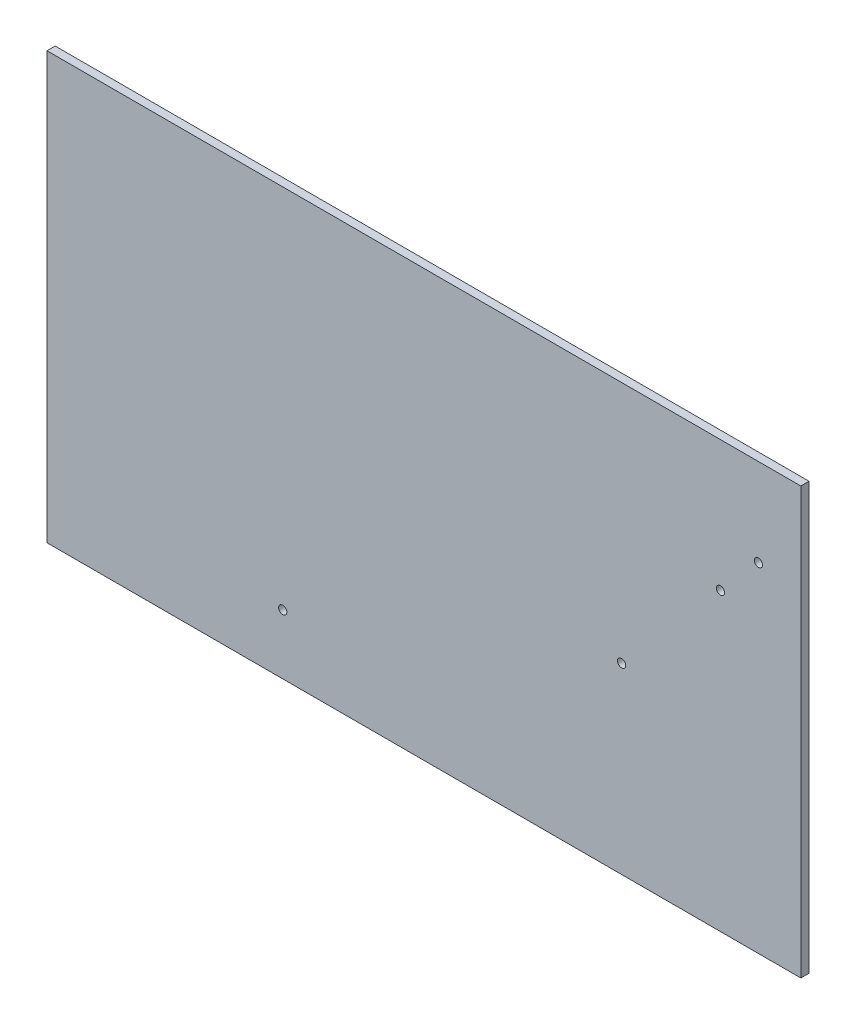
SolidWorks part; units mm, degrees
material "Thornel Mat VMA"
ref_plane "Front Plane" through (0, 0, 0) normal (0, 0, 1) x (1, 0, 0)
ref_plane "Top Plane" through (0, 0, 0) normal (0, 1, 0) x (1, 0, 0)
ref_plane "Right Plane" through (0, 0, 0) normal (1, 0, 0) x (0, 0, -1)
sketch "Sketch1" plane through (0, 0, 0) normal (0, 0, 1) x (1, 0, 0)
  line L0 (584.2, 0) -> (566.8254, 47.7364) construction
  line L3 (0, 330.2) -> (584.2, 330.2)
  line L5 (584.2, 330.2) -> (566.8254, 47.7364) construction
  line L6 (584.2, 0) -> (584.2, 330.2)
  line L7 (566.8254, 47.7364) -> (30.8772, 0.4906) construction
  line L8 (19.7249, 0) -> (0, 0) construction
  line L9 (0, 0) -> (0, 330.2)
  line L10 (0, 0) -> (584.2, 0)
  line L11 (182.7176, 46.2772) -> (445.2677, 141.8376) construction
  line L12 (551.2995, 262.3185) -> (521.9333, 228.9505) construction
  arc A0 (30.8772, 0.4906) -> (19.7249, 0) centre (19.7249, 127) cw construction
  circle A1 centre (182.7176, 46.2772) radius 3.175
  circle A2 centre (445.2677, 141.8376) radius 3.175
  circle A3 centre (521.9333, 228.9505) radius 3.175
  circle A4 centre (551.2995, 262.3185) radius 3.175
  spline S0 degree 2 poles (584.2, 330.2) (566.8254, 47.7364) (30.8772, 0.4906) knots 0 0 0 1 1 1 construction
  spline S1 degree 1 poles (558.8479, 331.7594) (28.6467, 25.7925) knots 0 0 1 1 construction
  spline S2 degree 2 poles (558.8479, 331.7594) (558.3508, 323.6772) (555.482, 300.2083) (548.0448, 270.8817) (537.017, 243.3493) (518.6822, 210.9611) (484.8837, 171.5386) (457.197, 150.374) (442.9828, 139.9187) (411.1198, 120.2243) (352.6628, 91.7959) (262.7906, 62.7429) (209.2344, 51.5081) (182.3957, 45.9179) (95.7948, 31.7202) (28.6467, 25.7925) knots 0 0 0 0.03125 0.09375 0.15625 0.21875 0.3125 0.426492 0.4375 0.488992 0.5625 0.6875 0.810672 0.8125 0.873172 1 1 1 construction
  spline S3 degree 1 poles (565.1859, 331.3696) (29.2043, 19.467) knots 0 0 1 1 construction
  spline S4 degree 2 poles (565.1859, 331.3696) (564.6773, 323.1011) (561.7388, 299.052) (556.0647, 276.672) (551.4155, 262.2627) (548.5091, 254.9645) (542.7528, 240.5906) (523.8915, 207.276) (487.3897, 164.7159) (429.5121, 122.1107) (354.9824, 85.8667) (263.7134, 56.3711) (128.7867, 28.2613) (29.2043, 19.467) knots 0 0 0 0.03125 0.09375 0.124079 0.155329 0.15625 0.21875 0.3125 0.4375 0.5625 0.6875 0.8125 1 1 1 construction
  dimension "D5" = 127
  dimension "D6" = 19.7249
  dimension "D10" = 6.35
  dimension "D11" = 6.35
  dimension "D14" = 6.35
  dimension "D15" = 6.35
  dimension "D1" = 330.2
  dimension "D2" = 584.2
  dimension "D3" = 160
  dimension "D4" = 50.8
  dimension "D7" = 25.4
  dimension "D8" = 279.4
  dimension "D9" = 160
  dimension "D13" = 44.45
  dimension "D16" = 69.85
  dimension "D12" = 19.05
extrude "Boss-Extrude1" add sketch "Sketch1" along normal blind 6.35
